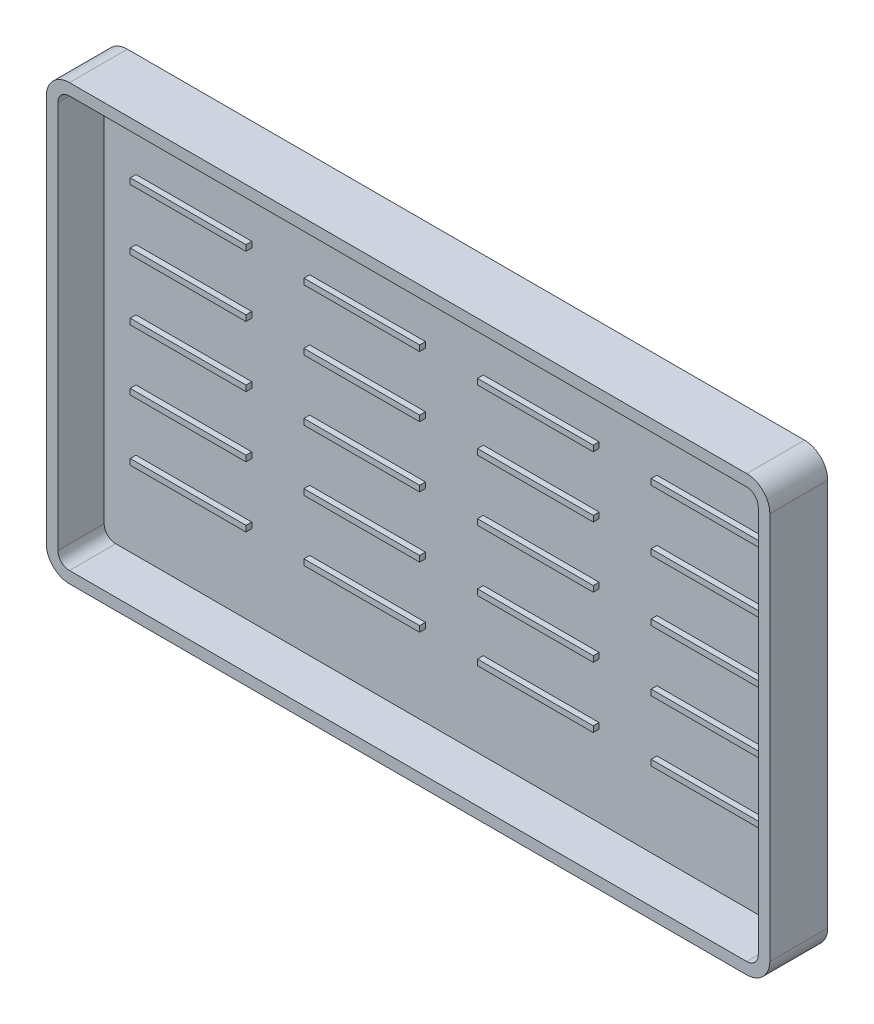
SolidWorks part; units mm, degrees
ref_plane "Front Plane" through (0, 0, 0) normal (0, 0, 1) x (1, 0, 0)
ref_plane "Top Plane" through (0, 0, 0) normal (0, 1, 0) x (1, 0, 0)
ref_plane "Right Plane" through (0, 0, 0) normal (1, 0, 0) x (0, 0, -1)
sketch "Sketch1" plane through (0, 0, 0) normal (0, 0, 1) x (1, 0, 0)
  line L1 (0, 0) -> (125, 0)
  line L2 (0, 0) -> (0, 75)
  line L3 (0, 75) -> (125, 75)
  line L4 (125, 0) -> (125, 75)
  dimension "D1" = 125
  dimension "D2" = 75
extrude "Boss-Extrude1" add sketch "Sketch1" along normal blind 10
fillet "Fillet1" radius 4 4 edges at (0, 75, 5) (0, 0, 5) (125, 0, 5) (125, 75, 5)
shell "Shell1" thickness 2
sketch "Sketch2" plane through (0, 0, 2) normal (0, 0, 1) x (1, 0, 0)
  line L5 (121, 73) -> (4, 73) construction
  line L42 (123, 4) -> (123, 71) construction
  line L43 (117.5, 59) -> (97.5, 59)
  line L44 (117.5, 59) -> (117.5, 58)
  line L45 (117.5, 58) -> (97.5, 58)
  line L46 (97.5, 59) -> (97.5, 58)
  line L47 (87.5, 59) -> (67.5, 59)
  line L48 (87.5, 59) -> (87.5, 58)
  line L49 (87.5, 58) -> (67.5, 58)
  line L50 (67.5, 59) -> (67.5, 58)
  line L51 (87.5, 48.5) -> (67.5, 48.5)
  line L52 (87.5, 48.5) -> (87.5, 47.5)
  line L53 (87.5, 47.5) -> (67.5, 47.5)
  line L54 (67.5, 48.5) -> (67.5, 47.5)
  line L55 (87.5, 38) -> (67.5, 38)
  line L56 (87.5, 38) -> (87.5, 37)
  line L57 (87.5, 37) -> (67.5, 37)
  line L58 (67.5, 38) -> (67.5, 37)
  line L59 (87.5, 27.5) -> (67.5, 27.5)
  line L60 (87.5, 27.5) -> (87.5, 26.5)
  line L61 (87.5, 26.5) -> (67.5, 26.5)
  line L62 (67.5, 27.5) -> (67.5, 26.5)
  line L63 (87.5, 17) -> (67.5, 17)
  line L64 (87.5, 17) -> (87.5, 16)
  line L65 (87.5, 16) -> (67.5, 16)
  line L66 (67.5, 17) -> (67.5, 16)
  line L67 (117.5, 48.5) -> (97.5, 48.5)
  line L68 (117.5, 48.5) -> (117.5, 47.5)
  line L69 (117.5, 47.5) -> (97.5, 47.5)
  line L70 (97.5, 48.5) -> (97.5, 47.5)
  line L71 (117.5, 38) -> (97.5, 38)
  line L72 (117.5, 38) -> (117.5, 37)
  line L73 (117.5, 37) -> (97.5, 37)
  line L74 (97.5, 38) -> (97.5, 37)
  line L75 (117.5, 27.5) -> (97.5, 27.5)
  line L76 (117.5, 27.5) -> (117.5, 26.5)
  line L77 (117.5, 26.5) -> (97.5, 26.5)
  line L78 (97.5, 27.5) -> (97.5, 26.5)
  line L79 (117.5, 17) -> (97.5, 17)
  line L80 (117.5, 17) -> (117.5, 16)
  line L81 (117.5, 16) -> (97.5, 16)
  line L82 (97.5, 17) -> (97.5, 16)
  line L84 (57.5, 59) -> (37.5, 59)
  line L85 (57.5, 59) -> (57.5, 58)
  line L86 (57.5, 58) -> (37.5, 58)
  line L87 (37.5, 59) -> (37.5, 58)
  line L88 (57.5, 48.5) -> (37.5, 48.5)
  line L89 (57.5, 48.5) -> (57.5, 47.5)
  line L90 (57.5, 47.5) -> (37.5, 47.5)
  line L91 (37.5, 48.5) -> (37.5, 47.5)
  line L92 (57.5, 38) -> (37.5, 38)
  line L93 (57.5, 38) -> (57.5, 37)
  line L94 (57.5, 37) -> (37.5, 37)
  line L95 (37.5, 38) -> (37.5, 37)
  line L96 (57.5, 27.5) -> (37.5, 27.5)
  line L97 (57.5, 27.5) -> (57.5, 26.5)
  line L98 (57.5, 26.5) -> (37.5, 26.5)
  line L99 (37.5, 27.5) -> (37.5, 26.5)
  line L100 (57.5, 17) -> (37.5, 17)
  line L101 (57.5, 17) -> (57.5, 16)
  line L102 (57.5, 16) -> (37.5, 16)
  line L103 (37.5, 17) -> (37.5, 16)
  line L109 (27.5, 59) -> (7.5, 59)
  line L110 (27.5, 59) -> (27.5, 58)
  line L111 (27.5, 58) -> (7.5, 58)
  line L112 (7.5, 59) -> (7.5, 58)
  line L113 (27.5, 48.5) -> (7.5, 48.5)
  line L114 (27.5, 48.5) -> (27.5, 47.5)
  line L115 (27.5, 47.5) -> (7.5, 47.5)
  line L116 (7.5, 48.5) -> (7.5, 47.5)
  line L117 (27.5, 38) -> (7.5, 38)
  line L118 (27.5, 38) -> (27.5, 37)
  line L119 (27.5, 37) -> (7.5, 37)
  line L120 (7.5, 38) -> (7.5, 37)
  line L121 (27.5, 27.5) -> (7.5, 27.5)
  line L122 (27.5, 27.5) -> (27.5, 26.5)
  line L123 (27.5, 26.5) -> (7.5, 26.5)
  line L124 (7.5, 27.5) -> (7.5, 26.5)
  line L125 (27.5, 17) -> (7.5, 17)
  line L126 (27.5, 17) -> (27.5, 16)
  line L127 (27.5, 16) -> (7.5, 16)
  line L128 (7.5, 17) -> (7.5, 16)
  line L133 (67.5, 59) -> (67.5, 58) [skipped]
  line L134 (67.5, 48.5) -> (67.5, 47.5) [skipped]
  line L135 (67.5, 38) -> (67.5, 37) [skipped]
  line L136 (67.5, 27.5) -> (67.5, 26.5) [skipped]
  line L137 (67.5, 17) -> (67.5, 16) [skipped]
  line L138 (37.5, 59) -> (37.5, 58) [skipped]
  line L139 (37.5, 48.5) -> (37.5, 47.5) [skipped]
  line L140 (37.5, 38) -> (37.5, 37) [skipped]
  line L141 (37.5, 27.5) -> (37.5, 26.5) [skipped]
  line L142 (37.5, 17) -> (37.5, 16) [skipped]
  dimension "D2" = 10
  dimension "D3" = 3
  dimension "D4" = 10
  dimension "D7" = 1
  dimension "D8" = 20
  dimension "D9" = 14
  dimension "D10" = 5.5
  dimension "D5" = 9.5
  dimension "D11" = 2
  dimension "D12" = 5
extrude "Boss-Extrude2" add sketch "Sketch2" along normal blind 1
